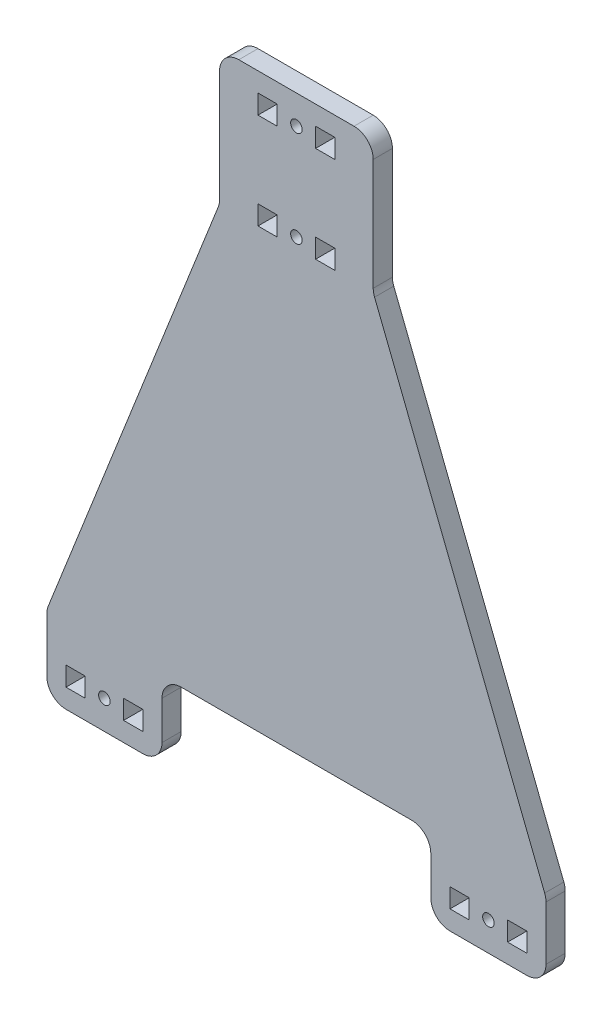
SolidWorks part; units mm, degrees
ref_plane "Front Plane" through (0, 0, 0) normal (0, 0, 1) x (1, 0, 0)
ref_plane "Top Plane" through (0, 0, 0) normal (0, 1, 0) x (1, 0, 0)
ref_plane "Right Plane" through (0, 0, 0) normal (1, 0, 0) x (0, 0, -1)
sketch "Sketch1" plane through (0, 0, 0) normal (0, 0, 1) x (1, 0, 0)
  line L0 (-50, 0) -> (50, 0) construction
  line L1 (-50, 124) -> (50, 124) construction
  line L2 (50, 124) -> (50, 0) construction
  line L3 (-50, 0) -> (-50, 124) construction
  line L4 (0, 124) -> (0, 0) construction
  line L5 (-65, -10) -> (-35, -10)
  line L6 (-35, -10) -> (-35, 10)
  line L7 (-35, 10) -> (35, 10)
  line L8 (35, 10) -> (35, -10)
  line L9 (35, -10) -> (65, -10)
  line L10 (65, -10) -> (65, 10)
  line L11 (65, 10) -> (20, 124)
  line L12 (20, 124) -> (20, 159)
  line L13 (20, 159) -> (-20, 159)
  line L14 (-20, 159) -> (-20, 124)
  line L15 (-20, 124) -> (-65, 10)
  line L16 (-65, 10) -> (-65, -10)
  line B0 (45, 0) -> (40, 0)
  line B1 (45, 0) -> (45, -5)
  line B2 (45, -5) -> (40, -5)
  line B3 (40, 0) -> (40, -5)
  line B4 (55, 0) -> (60, 0)
  line B5 (55, 0) -> (55, -5)
  line B6 (55, -5) -> (60, -5)
  line B7 (60, 0) -> (60, -5)
  line B8 (50, -2.5) -> (50, 4.4724) construction
  circle B9 centre (50, -2.5) radius 1.5
  line B10 (-55, 0) -> (-60, 0)
  line B11 (-55, 0) -> (-55, -5)
  line B12 (-55, -5) -> (-60, -5)
  line B13 (-60, 0) -> (-60, -5)
  line B14 (-45, 0) -> (-40, 0)
  line B15 (-45, 0) -> (-45, -5)
  line B16 (-45, -5) -> (-40, -5)
  line B17 (-40, 0) -> (-40, -5)
  line B18 (-50, -2.5) -> (-50, 4.4724) construction
  circle B19 centre (-50, -2.5) radius 1.5
  line B20 (-5, 129) -> (-10, 129)
  line B21 (-5, 129) -> (-5, 124)
  line B22 (-5, 124) -> (-10, 124)
  line B23 (-10, 129) -> (-10, 124)
  line B24 (5, 129) -> (10, 129)
  line B25 (5, 129) -> (5, 124)
  line B26 (5, 124) -> (10, 124)
  line B27 (10, 129) -> (10, 124)
  line B28 (0, 126.5) -> (0, 133.4724) construction
  circle B29 centre (0, 126.5) radius 1.5
  line B30 (-5, 154) -> (-10, 154)
  line B31 (-5, 154) -> (-5, 149)
  line B32 (-5, 149) -> (-10, 149)
  line B33 (-10, 154) -> (-10, 149)
  line B34 (5, 154) -> (10, 154)
  line B35 (5, 154) -> (5, 149)
  line B36 (5, 149) -> (10, 149)
  line B37 (10, 154) -> (10, 149)
  line B38 (0, 151.5) -> (0, 158.4724) construction
  circle B39 centre (0, 151.5) radius 1.5
  dimension "D1" = 50
  dimension "D2" = 124
  dimension "D3" = 20
  dimension "D4" = 10
  dimension "D5" = 10
  dimension "D6" = 5
  dimension "D7" = 5
  dimension "D8" = 5
  dimension "D9" = 5
  dimension "D10" = 5
  dimension "D11" = 5
  dimension "D12" = 5
  dimension "D13" = 10
  dimension "D14" = 10
  dimension "D15" = 10
sketch_block_instance "Trou M3 plots 5mm-1"
sketch_block "Trou M3 plots 5mm" parameters "D2"=3, "D1"=5, "D3"=5, "D4"=10
sketch_block_instance "Trou M3 plots 5mm-2"
sketch_block_instance "Trou M3 plots 5mm-3"
sketch_block_instance "Trou M3 plots 5mm-4"
extrude "Boss-Extrude1" add sketch "Sketch1" along normal blind 5
fillet "Fillet1" radius 5 12 edges at (-65, 10, 2.5) (-65, -10, 2.5) (-35, -10, 2.5) (-35, 10, 2.5) (35, 10, 2.5) (35, -10, 2.5) (65, -10, 2.5) (65, 10, 2.5) (20, 124, 2.5) (-20, 124, 2.5) (-20, 159, 2.5) (20, 159, 2.5)
